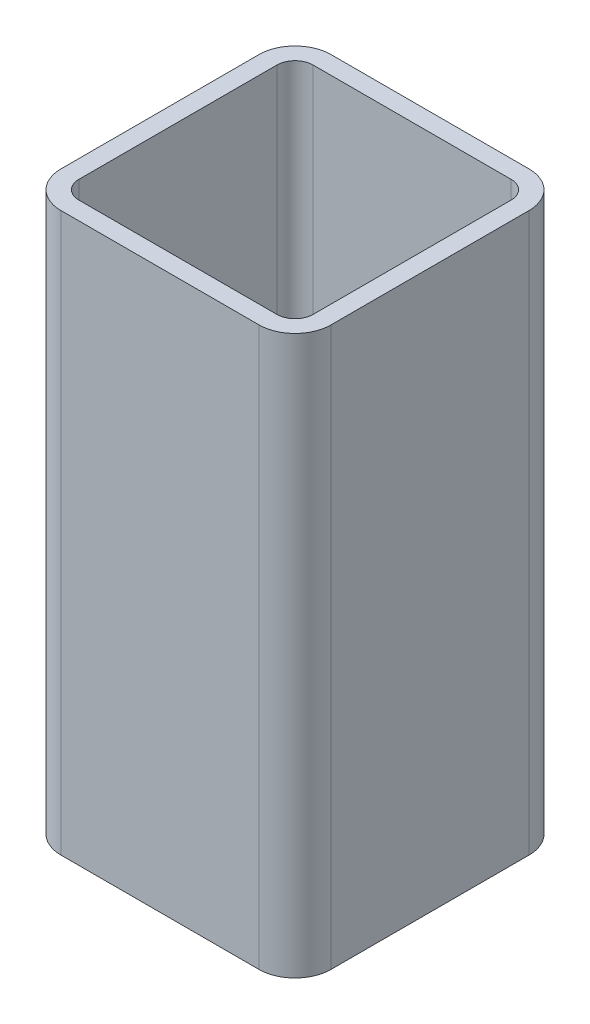
SolidWorks part; units mm, degrees
ref_plane "前视基准面" through (0, 0, 0) normal (0, 0, 1) x (1, 0, 0)
ref_plane "上视基准面" through (0, 0, 0) normal (0, 1, 0) x (1, 0, 0)
ref_plane "右视基准面" through (0, 0, 0) normal (1, 0, 0) x (0, 0, -1)
sketch "草图1" plane through (0, 0, 0) normal (0, 1, 0) x (1, 0, 0)
  line L0 (4, 2) -> (26, 2)
  line L1 (4, 0) -> (26, 0)
  line L2 (0, 4) -> (0, 26)
  line L3 (4, 30) -> (26, 30)
  line L4 (30, 4) -> (30, 26)
  line L5 (28, 4) -> (28, 26)
  line L6 (4, 28) -> (26, 28)
  line L7 (2, 4) -> (2, 26)
  arc A0 (4, 0) -> (0, 4) centre (4, 4) cw
  arc A1 (26, 0) -> (30, 4) centre (26, 4) ccw
  arc A2 (26, 30) -> (30, 26) centre (26, 26) cw
  arc A3 (0, 26) -> (4, 30) centre (4, 26) cw
  arc A4 (26, 2) -> (28, 4) centre (26, 4) ccw
  arc A5 (26, 28) -> (28, 26) centre (26, 26) cw
  arc A6 (2, 26) -> (4, 28) centre (4, 26) cw
  arc A7 (4, 2) -> (2, 4) centre (4, 4) cw
  point P7 (0, 0)
  point P10 (30, 0)
  point P13 (30, 30)
  point P16 (0, 30)
  dimension "D3" = 4
  dimension "D1" = 30
  dimension "D2" = 30
  dimension "D4" = 2
extrude "凸台-拉伸1" add sketch "草图1" along normal blind 62
